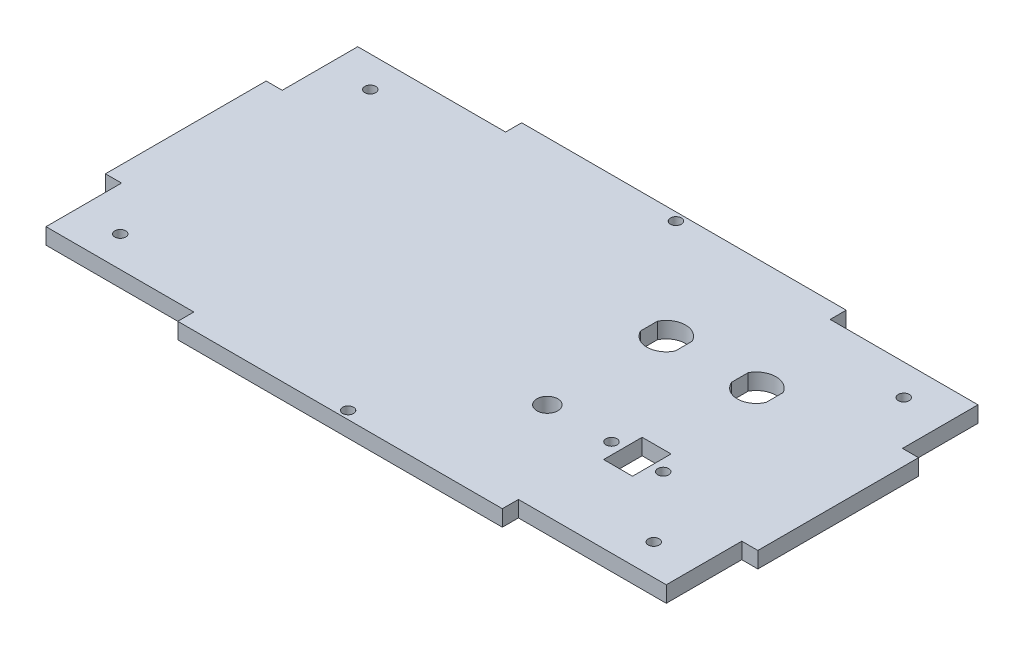
SolidWorks part; units mm, degrees
ref_plane "Front Plane" through (0, 0, 0) normal (0, 0, 1) x (1, 0, 0)
ref_plane "Top Plane" through (0, 0, 0) normal (0, 1, 0) x (1, 0, 0)
ref_plane "Right Plane" through (0, 0, 0) normal (1, 0, 0) x (0, 0, -1)
sketch "Sketch1" plane through (0, 0, 0) normal (0, 1, 0) x (1, 0, 0)
  line L1 (0, 0) -> (203, 0)
  line L2 (0, 0) -> (0, 107)
  line L3 (0, 107) -> (203, 107)
  line L4 (203, 0) -> (203, 107)
  dimension "D1" = 107
  dimension "D2" = 203
extrude "Boss-Extrude1" add sketch "Sketch1" along normal blind 5
sketch "Sketch3" plane through (0, 5, 0) normal (0, 1, 0) x (1, 0, 0)
  line L0 (203, 107) -> (0, 107) construction
  line L1 (51, 107) -> (0, 107)
  line L2 (51, 107) -> (51, 102)
  line L3 (51, 102) -> (0, 102)
  line L4 (0, 107) -> (0, 102)
  line L5 (0, 107) -> (0, 0) construction
  line L6 (203, 0) -> (203, 107) construction
  line L7 (203, 107) -> (152, 107)
  line L8 (203, 107) -> (203, 102)
  line L9 (203, 102) -> (152, 102)
  line L10 (152, 107) -> (152, 102)
  line L11 (0, 0) -> (51, 0)
  line L12 (0, 0) -> (0, 5)
  line L13 (0, 5) -> (51, 5)
  line L14 (51, 0) -> (51, 5)
  line L15 (203, 0) -> (152, 0)
  line L16 (203, 0) -> (203, 5)
  line L17 (203, 5) -> (152, 5)
  line L18 (152, 0) -> (152, 5)
  dimension "D1" = 51
  dimension "D2" = 5
  dimension "D3" = 51
  dimension "D4" = 5
  dimension "D5" = 5
  dimension "D6" = 51
  dimension "D7" = 5
  dimension "D8" = 51
  dimension "D9" = 51
extrude "Cut-Extrude1" cut sketch "Sketch3" against normal through all
sketch "Sketch4" plane through (0, 5, 0) normal (0, 1, 0) x (1, 0, 0)
  line L0 (0, 102) -> (0, 5) construction
  line L1 (0, 78.5) -> (5, 78.5)
  line L2 (0, 78.5) -> (0, 107)
  line L3 (0, 107) -> (5, 107)
  line L4 (5, 78.5) -> (5, 107)
  line L5 (152, 107) -> (51, 107) construction
  line L6 (203, 5) -> (203, 102) construction
  line L7 (0, 0) -> (5, 0)
  line L8 (0, 0) -> (0, 28.5)
  line L9 (0, 28.5) -> (5, 28.5)
  line L10 (5, 0) -> (5, 28.5)
  line L11 (203, 28.5) -> (198, 28.5)
  line L12 (203, 28.5) -> (203, 0)
  line L13 (203, 0) -> (198, 0)
  line L14 (198, 28.5) -> (198, 0)
  line L15 (203, 5) -> (203, 102) construction
  line L16 (203, 107) -> (198, 107)
  line L17 (203, 107) -> (203, 78.5)
  line L18 (203, 78.5) -> (198, 78.5)
  line L19 (198, 107) -> (198, 78.5)
  line L20 (203, 5) -> (152, 5) construction
  line L21 (152, 102) -> (203, 102) construction
  line L22 (51, 5) -> (0, 5) construction
  dimension "D1" = 5
  dimension "D2" = 28.5
  dimension "D3" = 28.5
  dimension "D4" = 28.5
  dimension "D5" = 5
  dimension "D6" = 5
  dimension "D7" = 28.5
  dimension "D8" = 5
  dimension "D9" = 28.5
  dimension "D10" = 0
  dimension "D11" = 5
  dimension "D12" = 5
  dimension "D13" = 5
extrude "Cut-Extrude2" cut sketch "Sketch4" against normal through all
sketch "Sketch7" plane through (0, 0, 0) normal (0, -1, 0) x (1, 0, 0)
  line L0 (164.3851, -69.6835) -> (164.3851, -74.9455)
  line L2 (153.5851, -69.754) -> (153.5851, -74.8903)
  line L3 (203, -28.5) -> (203, -78.5) construction
  line L4 (152, -107) -> (51, -107) construction
  line L6 (136.4, -69.4023) -> (136.4, -74.6329)
  line L10 (125.6, -69.4023) -> (125.6, -74.6329)
  arc A0 (164.3851, -69.6835) -> (153.5851, -69.754) centre (159, -72) ccw
  arc A1 (136.4, -69.4023) -> (125.6, -69.4023) centre (131, -72) ccw
  arc A2 (125.6, -74.6329) -> (136.4, -74.6329) centre (131, -72) ccw
  arc A3 (153.5851, -74.8903) -> (164.3851, -74.9455) centre (159, -72) ccw
  point P1 (158.9617, -66.1379)
  point P2 (158.9687, -78.1379)
  point P3 (131, -66.0077)
  point P7 (131, -78.0077)
  dimension "D1" = 12
  dimension "D5" = 72
  dimension "D2" = 35
  dimension "D3" = 10.8
  dimension "D4" = 28
  dimension "D6" = 35
  dimension "D8" = 10.8
  dimension "D9" = 12
extrude "Cut-Extrude3" cut sketch "Sketch7" against normal through all
sketch "Sketch10" plane through (0, 0, 0) normal (0, -1, 0) x (1, 0, 0)
  line L0 (51, 0) -> (152, 0) construction
  line L2 (203, -28.5) -> (203, -78.5) construction
  circle A0 centre (131, -35) radius 3.25
  dimension "D1" = 72
  dimension "D4" = 6.5
  dimension "D2" = 35
extrude "Cut-Extrude4" cut sketch "Sketch10" against normal through all
hole_wizard "M3 Clearance Hole1" positions "Sketch11" profile "Sketch12" hole size "M3" standard "ANSI Metric" end condition through all
sketch "Sketch11" plane through (0, 0, 0) normal (0, -1, 0) x (-1, 0, 0)
  line L6 (-5, 5) -> (-5, 28.5) construction
  line L7 (-51, 5) -> (-5, 5) construction
  line L8 (-5, 102) -> (-51, 102) construction
  line L9 (-152, 102) -> (-198, 102) construction
  line L10 (-198, 5) -> (-152, 5) construction
  line L11 (-198, 28.5) -> (-198, 5) construction
  line L12 (-198, 102) -> (-198, 78.5) construction
  line L13 (-5, 78.5) -> (-5, 102) construction
  point P0 (-18.5, 14.6)
  point P4 (-184.5, 14.6)
  point P6 (-184.5, 92.4)
  point P10 (-18.5, 92.4)
  dimension "D3" = 77.8
  dimension "D6" = 77.8
  dimension "D7" = 13.5
  dimension "D8" = 9.6
  dimension "D9" = 166
  dimension "D10" = 166
  dimension "D12" = 183.3271
  dimension "D13" = 183.3271
  dimension "D14" = 9.6
  dimension "D15" = 9.6
  dimension "D16" = 9.6
  dimension "D17" = 13.5
  dimension "D18" = 13.5
  dimension "D19" = 13.5
sketch "Sketch12" plane through (18.5, 0, -14.6) normal (1, 0, 0) x (0, 0, -1)
  line L0 (0, 0) -> (0, 5)
  line L1 (0, 5) -> (1.7, 5)
  line L2 (1.7, 5) -> (1.7, 0)
  line L5 (1.7, 0) -> (0, 0)
  line L11 (0, -6.35) -> (0, 107.95) construction
  dimension "Thru Hole Dia." = 3.4
  dimension "Thru Hole Depth" = 5
sketch "Sketch13" plane through (0, 0, 0) normal (0, -1, 0) x (-1, 0, 0)
  line L1 (-154.5, 29) -> (-163.5, 29)
  line L2 (-154.5, 29) -> (-154.5, 41)
  line L3 (-154.5, 41) -> (-163.5, 41)
  line L4 (-163.5, 29) -> (-163.5, 41)
  line L5 (-203, 28.5) -> (-203, 78.5) construction
  line L6 (-51, 0) -> (-152, 0) construction
  point P4 (-154.5, 35)
  point P9 (-159, 29)
  dimension "D1" = 12
  dimension "D2" = 9
  dimension "D3" = 35
  dimension "D4" = 44
extrude "Cut-Extrude5" cut sketch "Sketch13" against normal through all
hole_wizard "M3 Clearance Hole2" positions "Sketch15" profile "Sketch16" hole size "M3" standard "ANSI Metric" end condition through all
sketch "Sketch15" plane through (0, 0, 0) normal (0, -1, 0) x (-1, 0, 0)
  line L0 (-154.5, 29) -> (-154.5, 41) construction
  line L1 (-163.5, 29) -> (-154.5, 29) construction
  line L2 (-163.5, 41) -> (-163.5, 29) construction
  point P0 (-150.95, 35)
  point P8 (-167.05, 35)
  dimension "D3" = 6
  dimension "D4" = 3.55
  dimension "D6" = 6
  dimension "D7" = 3.55
sketch "Sketch16" plane through (150.95, 0, -35) normal (1, 0, 0) x (0, 0, -1)
  line L0 (0, 0) -> (0, 5)
  line L1 (0, 5) -> (1.7, 5)
  line L2 (1.7, 5) -> (1.7, 0)
  line L5 (1.7, 0) -> (0, 0)
  line L11 (0, -6.35) -> (0, 107.95) construction
  dimension "Thru Hole Dia." = 3.4
  dimension "Thru Hole Depth" = 5
hole_wizard "M3 Clearance Hole3" positions "Sketch17" profile "Sketch18" hole size "M3" standard "ANSI Metric" end condition through all
sketch "Sketch17" plane through (0, 0, 0) normal (0, -1, 0) x (-1, 0, 0)
  line L0 (-51, 0) -> (-51, 5) construction
  line L1 (-51, 102) -> (-51, 107) construction
  line L2 (-152, 107) -> (-51, 107) construction
  line L3 (-51, 0) -> (-152, 0) construction
  point P0 (-101.5, 104.5)
  point P2 (-101.5, 2.5)
  point P7 (-51, 2.5)
  dimension "D1" = 50.5
  dimension "D2" = 50.5
  dimension "D3" = 2.5
  dimension "D4" = 2.5
sketch "Sketch18" plane through (101.5, 0, -104.5) normal (1, 0, 0) x (0, 0, -1)
  line L0 (0, 0) -> (0, 5)
  line L1 (0, 5) -> (1.7, 5)
  line L2 (1.7, 5) -> (1.7, 0)
  line L5 (1.7, 0) -> (0, 0)
  line L11 (0, -6.35) -> (0, 107.95) construction
  dimension "Thru Hole Dia." = 3.4
  dimension "Thru Hole Depth" = 5
